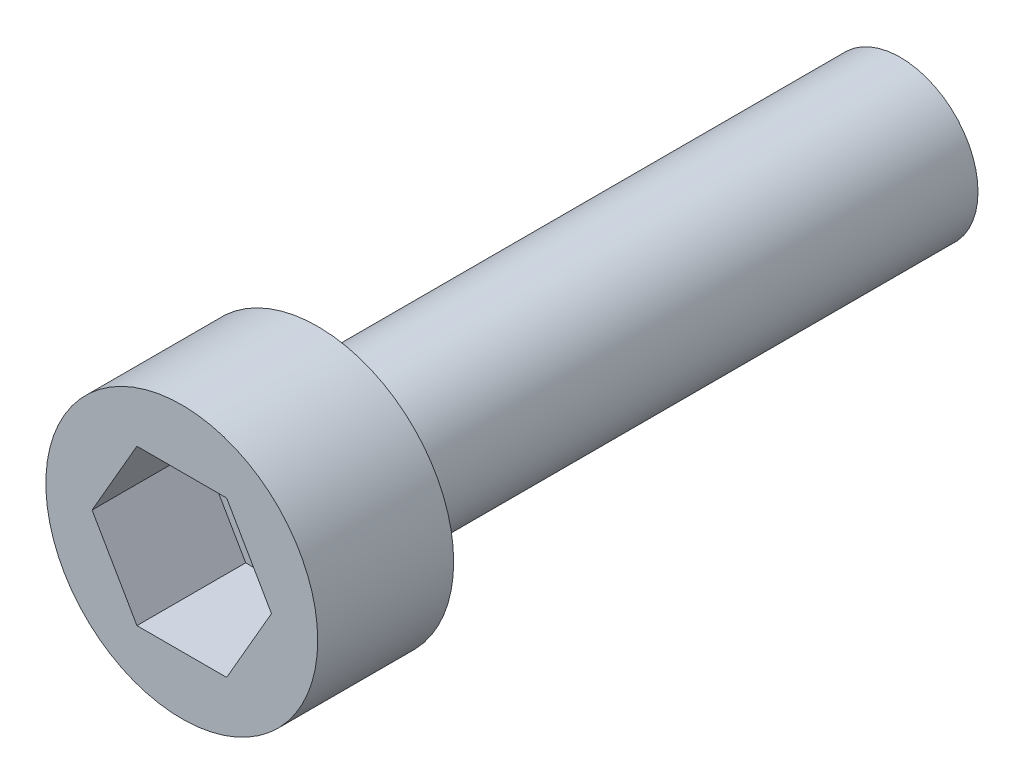
SolidWorks part; units mm, degrees
ref_plane "Front Plane" through (0, 0, 0) normal (0, 0, 1) x (1, 0, 0)
ref_plane "Top Plane" through (0, 0, 0) normal (0, 1, 0) x (1, 0, 0)
ref_plane "Right Plane" through (0, 0, 0) normal (1, 0, 0) x (0, 0, -1)
sketch "Sketch1" plane through (0, 0, 0) normal (0, 0, 1) x (1, 0, 0)
  circle A0 centre (0, 0) radius 3.5
  dimension "D1" = 7
extrude "Head Boss-Extrude1" add sketch "Sketch1" along normal blind 3.5
sketch "Sketch3" plane through (0, 0, 3.5) normal (0, 0, 1) x (1, 0, 0)
  line L0 (-1.1547, 2) -> (1.1547, 2)
  line L1 (1.1547, 2) -> (2.3094, 0)
  line L2 (2.3094, 0) -> (1.1547, -2)
  line L3 (1.1547, -2) -> (-1.1547, -2)
  line L4 (-1.1547, -2) -> (-2.3094, 0)
  line L5 (-2.3094, 0) -> (-1.1547, 2)
  line L6 (-2.3094, 0) -> (0, 0) construction
  line L7 (2.3094, 0) -> (0, 0) construction
  line L8 (-1.1547, -2) -> (0, 0) construction
  line L9 (0, 0) -> (1.1547, 2) construction
  line L10 (-1.1547, 2) -> (0, 0) construction
  line L11 (0, 0) -> (1.1547, -2) construction
  dimension "D1" = 60
  dimension "D2" = 60
  dimension "D3" = 60
  dimension "D4" = 60
  dimension "D5" = 60
  dimension "D6" = 4
extrude "Head Hex Cut-Extrude1" cut sketch "Sketch3" against normal blind 2.8
sketch "Sketch2" plane through (0, 0, 0) normal (0, 0, 1) x (1, 0, 0)
  circle A0 centre (0, 0) radius 2
  dimension "D1" = 4
extrude "Screw Boss-Extrude2" add sketch "Sketch2" against normal blind 15
